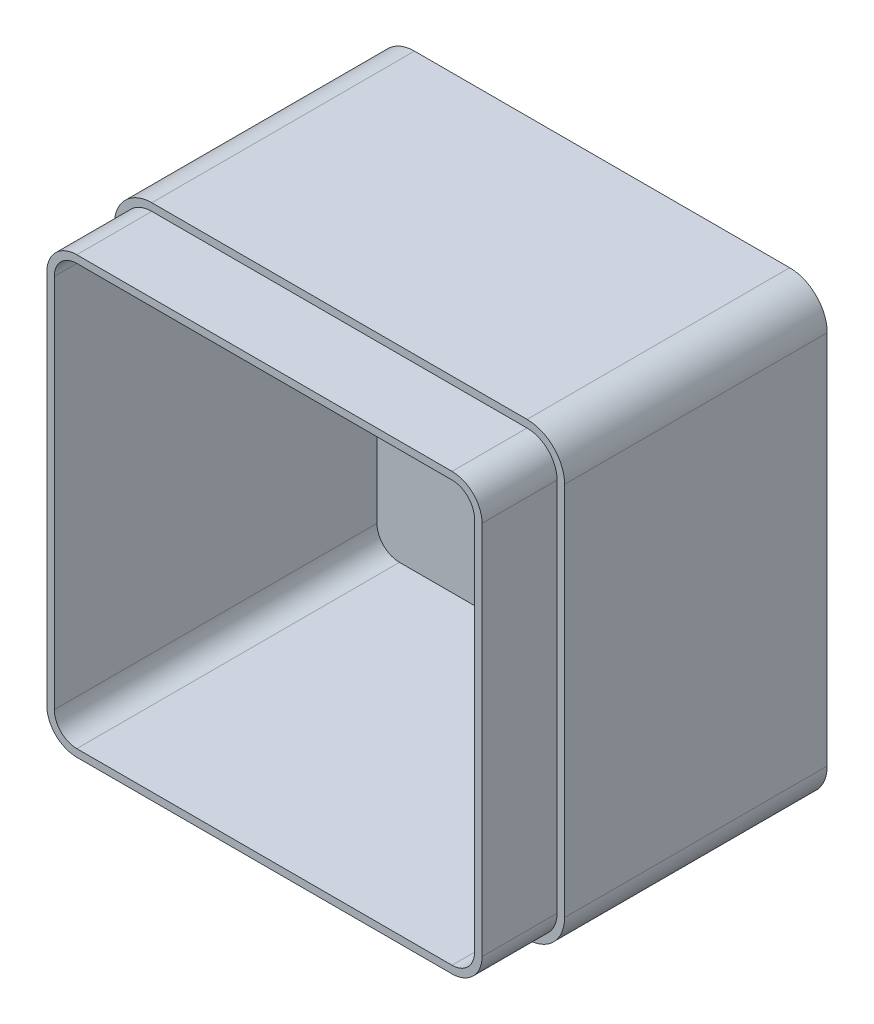
SolidWorks part; units mm, degrees
ref_plane "Front" through (0, 0, 0) normal (0, 0, 1) x (1, 0, 0)
ref_plane "Top" through (0, 0, 0) normal (0, 1, 0) x (1, 0, 0)
ref_plane "Right" through (0, 0, 0) normal (1, 0, 0) x (0, 0, -1)
sketch "Sketch1" plane through (0, 0, 0) normal (0, 0, 1) x (1, 0, 0)
  line L5 (0, 0) -> (120, 0)
  line L6 (0, 0) -> (0, 120)
  line L7 (0, 120) -> (120, 120)
  line L8 (120, 0) -> (120, 120)
  dimension "D1" = 120
  dimension "D2" = 120
extrude "Boss-Extrude1" add sketch "Sketch1" along normal blind 90
fillet "Fillet1" radius 10 4 edges at (120, 120, 45) (120, 0, 45) (0, 0, 45) (0, 120, 45)
shell "Shell1" thickness 4
sketch "Sketch2" plane through (0, 0, 90) normal (0, 0, 1) x (1, 0, 0)
  line L4 (120, 10) -> (120, 110)
  line L5 (110, 120) -> (10, 120)
  line L6 (0, 110) -> (0, 10)
  line L7 (10, 0) -> (110, 0)
  line L8 (120, 10) -> (120, 110)
  line L9 (110, 120) -> (10, 120)
  line L10 (0, 110) -> (0, 10)
  line L11 (10, 0) -> (110, 0)
  line L16 (118, 10) -> (118, 110)
  line L17 (110, 118) -> (10, 118)
  line L18 (2, 110) -> (2, 10)
  line L19 (10, 2) -> (110, 2)
  line L20 (118, 10) -> (118, 110)
  line L21 (110, 118) -> (10, 118)
  line L22 (2, 110) -> (2, 10)
  line L23 (10, 2) -> (110, 2)
  arc A4 (120, 110) -> (110, 120) centre (110, 110) ccw
  arc A5 (10, 120) -> (0, 110) centre (10, 110) ccw
  arc A6 (0, 10) -> (10, 0) centre (10, 10) ccw
  arc A7 (110, 0) -> (120, 10) centre (110, 10) ccw
  arc A8 (120, 110) -> (110, 120) centre (110, 110) ccw
  arc A9 (10, 120) -> (0, 110) centre (10, 110) ccw
  arc A10 (0, 10) -> (10, 0) centre (10, 10) ccw
  arc A11 (110, 0) -> (120, 10) centre (110, 10) ccw
  arc A16 (118, 110) -> (110, 118) centre (110, 110) ccw
  arc A17 (10, 118) -> (2, 110) centre (10, 110) ccw
  arc A18 (2, 10) -> (10, 2) centre (10, 10) ccw
  arc A19 (110, 2) -> (118, 10) centre (110, 10) ccw
  arc A20 (118, 110) -> (110, 118) centre (110, 110) ccw
  arc A21 (10, 118) -> (2, 110) centre (10, 110) ccw
  arc A22 (2, 10) -> (10, 2) centre (10, 10) ccw
  arc A23 (110, 2) -> (118, 10) centre (110, 10) ccw
  dimension "D1" = 0
  dimension "D2" = 2
extrude "Cut-Extrude1" cut sketch "Sketch2" against normal blind 20
